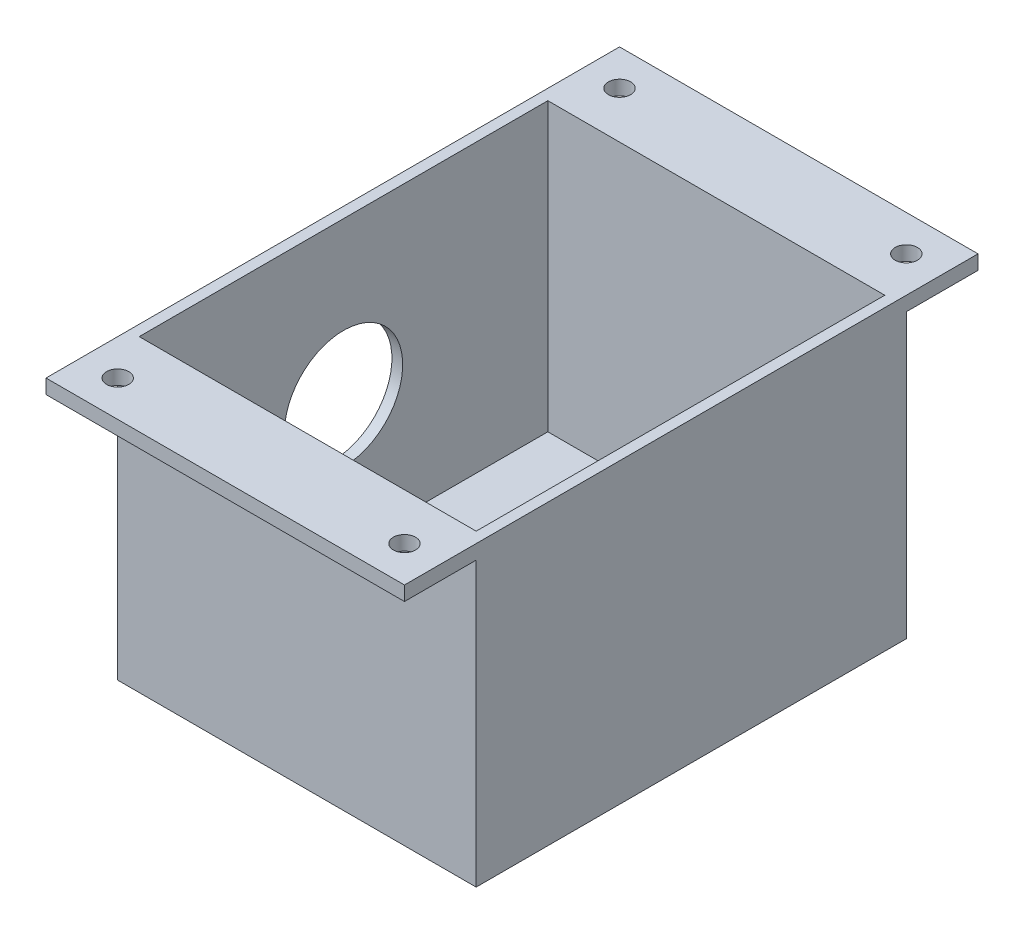
SolidWorks part; units mm, degrees
ref_plane "Płaszczyzna przednia" through (0, 0, 0) normal (0, 0, 1) x (1, 0, 0)
ref_plane "Płaszczyzna górna" through (0, 0, 0) normal (0, 1, 0) x (1, 0, 0)
ref_plane "Płaszczyzna prawa" through (0, 0, 0) normal (1, 0, 0) x (0, 0, -1)
sketch "Sketch1" plane through (0, 0, 0) normal (0, 1, 0) x (1, 0, 0)
  line L9 (-25, -40) -> (25, -40)
  line L16 (-25, -40) -> (-25, 40)
  line L21 (-25, 40) -> (25, 40)
  line L23 (25, -40) -> (25, 40)
  line L24 (-23.5, -28.5) -> (23.5, -28.5)
  line L25 (-23.5, -28.5) -> (-23.5, 28.5)
  line L26 (-25, -30) -> (25, -30)
  line L27 (-25, -30) -> (-25, 30)
  line L28 (-25, 30) -> (25, 30)
  line L29 (25, -30) -> (25, 30)
  line L30 (-23.5, 28.5) -> (23.5, 28.5)
  line L31 (23.5, -28.5) -> (23.5, 28.5)
  line L32 (-23.5, -28.5) -> (23.5, 28.5) construction
  line L33 (-23.5, 28.5) -> (23.5, -28.5) construction
  point P0 (0, 0)
  point P1 (0, 0)
  point P5 (0, 0)
  point P8 (0, 0)
  point P11 (0, 0)
  point P14 (0, 0)
  dimension "D1" = 50
  dimension "D2" = 80
  dimension "D3" = 50
  dimension "D4" = 60
  dimension "D5" = 47
  dimension "D6" = 57
extrude "Boss-Extrude6" add sketch "Sketch1" along normal blind 40 contours L28 L16 L26 L23 L31 L24 L25 L30
sketch "Sketch7" plane through (0, 0, 0) normal (0, -1, 0) x (1, 0, 0)
  line L1 (-25, 30) -> (25, 30)
  line L2 (-25, 30) -> (-25, -30)
  line L3 (-25, -30) -> (25, -30)
  line L4 (25, 30) -> (25, -30)
extrude "Boss-Extrude8" add sketch "Sketch7" along normal blind 1.5
sketch "Sketch8" plane through (25, 0, 0) normal (1, 0, 0) x (0, 0, -1)
  line L1 (-30, 40) -> (-40, 40)
  line L2 (-30, 40) -> (-30, 38)
  line L3 (-30, 38) -> (-40, 38)
  line L4 (-40, 40) -> (-40, 38)
  line L5 (30, 40) -> (40, 40)
  line L6 (30, 40) -> (30, 38)
  line L7 (30, 38) -> (40, 38)
  line L8 (40, 40) -> (40, 38)
  dimension "D1" = 10
  dimension "D2" = 2
  dimension "D3" = 10
  dimension "D4" = 2
extrude "Boss-Extrude9" add sketch "Sketch8" against normal blind 50
sketch "Sketch9" plane through (0, 40, 0) normal (0, 1, 0) x (1, 0, 0)
  circle A0 centre (-20, 35) radius 1.55
  circle A1 centre (20, 35) radius 1.55
  circle A2 centre (20, -35) radius 1.55
  circle A3 centre (-20, -35) radius 1.55
  point P0 (0, 0)
  dimension "D1" = 40
  dimension "D2" = 70
extrude "Cut-Extrude1" cut sketch "Sketch9" against normal blind 3
sketch "Sketch11" plane through (-25, 0, 0) normal (-1, 0, 0) x (0, 0, 1)
  line L0 (-30, 18.25) -> (30, 18.25) construction
  line L1 (-30, 38) -> (-30, -1.5) construction
  line L2 (30, 38) -> (30, -1.5) construction
  line L4 (40, 40) -> (-40, 40) construction
  line L5 (0, 40) -> (0, -1.5) construction
  line L6 (30, -1.5) -> (-30, -1.5) construction
  circle A0 centre (0, 18.25) radius 8.25
  point P6 (0, 18.25)
extrude "Cut-Extrude3" cut sketch "Sketch11" against normal blind 1.5
